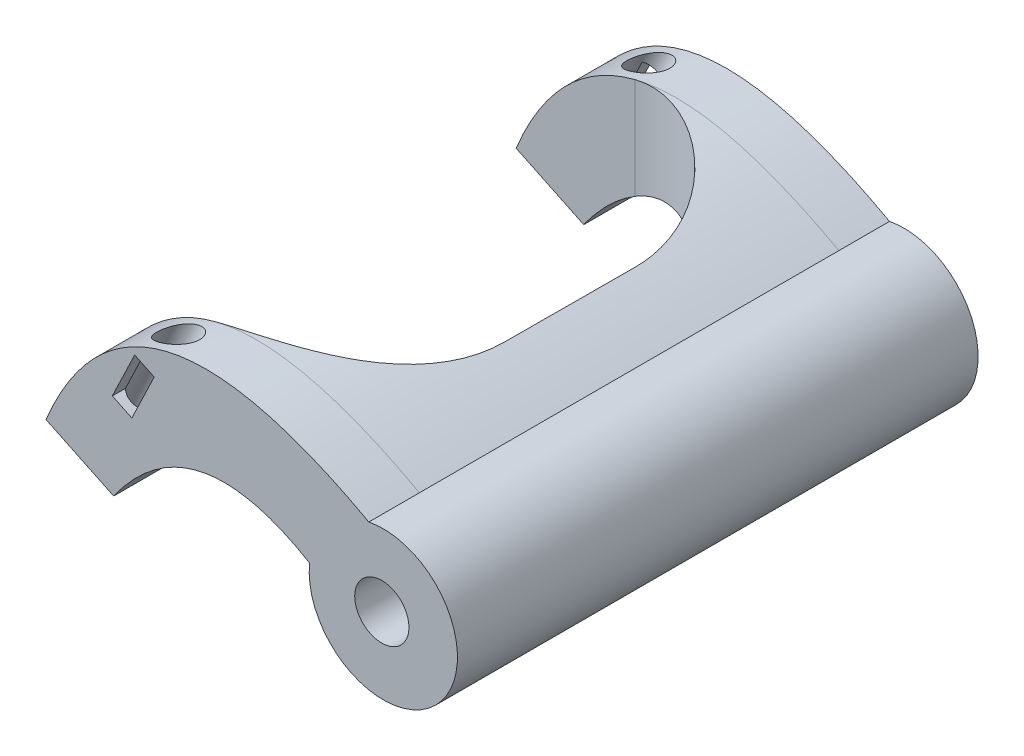
SolidWorks part; units mm, degrees
ref_plane "Front Plane" through (0, 0, 0) normal (0, 0, 1) x (1, 0, 0)
ref_plane "Top Plane" through (0, 0, 0) normal (0, 1, 0) x (1, 0, 0)
ref_plane "Right Plane" through (0, 0, 0) normal (1, 0, 0) x (0, 0, -1)
sketch "Sketch1" plane through (0, 0, 0) normal (0, 0, 1) x (1, 0, 0)
  circle A0 centre (0, 0) radius 10.25
  dimension "D1" = 20.5
extrude "Boss-Extrude1" add sketch "Sketch1" along normal blind 7
sketch "Sketch2" plane through (0, 0, 0) normal (0, 0, -1) x (-1, 0, 0)
  circle A0 centre (0.2048, 0.2011) radius 3.75 construction
  circle A1 centre (0.2048, 0.2011) radius 3.75
extrude "Cut-Extrude1" cut sketch "Sketch2" against normal blind 2
sketch "Sketch3" plane through (0, 0, 7) normal (0, 0, 1) x (1, 0, 0)
  line L0 (-30.4569, -15.3077) -> (-46.0317, -8.4941) construction
  line L1 (-66.2845, -97.2038) -> (-12.372, 26.0315) construction
  dimension "D1" = 17
sketch "Sketch4" plane through (0, 0, 7) normal (0, 0, 1) x (1, 0, 0)
  line L3 (-46.6405, 0) -> (-37.2823, -4.482)
  circle A0 centre (0, 0) radius 10.25 construction
  arc A5 (-2.0041, 10.0522) -> (-10.1965, 1.0454) centre (0, 0) ccw
  spline S0 degree 2 poles (-10.1965, 1.0454) (-26.4683, 10.7033) (-37.2823, -4.482) knots 0 0 0 1 1 1
  spline S1 degree 2 poles (-46.6405, 0) (-34.962, 28.1074) (-2.0041, 10.0522) knots 0 0 0 1 1 1
extrude "Boss-Extrude3" add sketch "Sketch4" against normal blind 7
ref_plane "Plane1" through (0, 0, 3.5) normal (0, 0, 1) x (1, 0, 0)
sketch "Sketch11" plane through (-8.7023, -18.17, 0) normal (-0.432, -0.9019, 0) x (0, 0, 1)
  line L0 (0, 31.6888) -> (7, 31.6888) construction
  line L1 (7, 42.0649) -> (7, 31.6888) construction
  circle A0 centre (3.5, 35.4988) radius 2.25
  dimension "D3" = 4.5
  dimension "D2" = 3.5
  dimension "D1" = 3.81
extrude "Cut-Extrude3" cut sketch "Sketch11" against normal blind 30
sketch "Sketch13" plane through (0, 0, 0) normal (0, 0, -1) x (-1, 0, 0)
  line L4 (34.3792, 13.8726) -> (31.6767, 12.5782)
  line L6 (34.7702, 6.1191) -> (37.4727, 7.4135)
  line L7 (37.4727, 7.4135) -> (34.3792, 13.8726)
  line L10 (31.6767, 12.5782) -> (34.7702, 6.1191)
  line L11 (32.4707, 12.0698) -> (36.7902, 3.0508) construction
  line L12 (35.9901, 9.3516) -> (34.2745, 12.9337) construction
  dimension "D1" = 0.4965
  dimension "D2" = 0.5
extrude "Cut-Extrude4" cut sketch "Sketch13" against normal blind 3
sketch "Sketch15" plane through (0, 0, 7) normal (0, 0, 1) x (1, 0, 0)
  circle A0 centre (0, 0) radius 10.25
extrude "Boss-Extrude4" add sketch "Sketch15" along normal blind 65
ref_plane "Plane2" through (0, 0, 36) normal (0, 0, 1) x (1, 0, 0)
mirror "Mirror1" about plane through (0, 0, 36) normal (0, 0, 1) of "Cut-Extrude1", "Cut-Extrude4", "Boss-Extrude3", "Cut-Extrude3"
sketch "Sketch18" plane through (0, 0, 7) normal (0, 0, 1) x (1, 0, 0)
  line L1 (-46.6405, 0) -> (-37.2823, -4.482)
  line L2 (-46.6405, 0) -> (-37.2823, -4.482)
  arc A1 (-2.0041, 10.0522) -> (-10.1965, 1.0454) centre (0, 0) ccw
  arc A2 (-2.0041, 10.0522) -> (-10.1965, 1.0454) centre (0, 0) ccw
  parabola Q2 (-2.0041, 10.0522) -> (-46.6405, 0) focus (-29.5281, 6.2713) apex (-33.6503, 15.2138)
  parabola Q3 (-37.2823, -4.482) -> (-10.1965, 1.0454) focus (-23.7122, -2.8884) apex (-25.3235, 4.446)
  parabola Q4 (-2.0041, 10.0522) -> (-46.6405, 0) focus (-29.5281, 6.2713) apex (-33.6503, 15.2138)
  parabola Q5 (-37.2823, -4.482) -> (-10.1965, 1.0454) focus (-23.7122, -2.8884) apex (-25.3235, 4.446)
  dimension "D1" = 0
extrude "Boss-Extrude5" add sketch "Sketch18" along normal up to vertex (58 mm away) up to point (-46.6405, 0, 65)
sketch "Sketch19" plane through (0, 0, 0) normal (0, 1, 0) x (1, 0, 0)
  line L0 (-10.1965, -7) -> (-37.2823, -7) construction
  line L1 (-56.8466, -7) -> (-30.1965, -7)
  line L2 (-56.8466, -7) -> (-56.8466, -65)
  line L3 (-56.8466, -65) -> (-30.25, -65)
  line L5 (-10.1965, -65) -> (-37.2823, -65) construction
  line L6 (-10.25, 0) -> (-10.25, -72) construction
  line L7 (-10.1965, -65) -> (-10.1965, -7) construction
  line L8 (-10.1965, -27) -> (-10.25, -45)
  arc A0 (-10.1965, -27) -> (-30.1965, -7) centre (-30.1965, -27) ccw
  arc A1 (-30.25, -65) -> (-10.25, -45) centre (-30.25, -45) ccw
  dimension "D1" = 40
  dimension "D2" = 40
extrude "Cut-Extrude5" cut sketch "Sketch19" along normal blind 44 and the other way blind 34
sketch "Sketch20" plane through (0, 0, 36) normal (0, 0, 1) x (1, 0, 0)
  circle A0 centre (0, 0) radius 10.25
  arc A1 (-10.1965, 1.0454) -> (-2.0041, 10.0522) centre (0, 0) ccw construction
extrude "Boss-Extrude6" add sketch "Sketch20" along normal blind 15 and the other way blind 20
sketch "Sketch21" plane through (0, 0, 70) normal (0, 0, 1) x (1, 0, 0)
  circle A1 centre (-0.2048, 0.2011) radius 3.75
  circle A2 centre (-0.2048, 0.2011) radius 3.75
  dimension "D1" = 0
extrude "Cut-Extrude6" cut sketch "Sketch21" against normal blind 92
